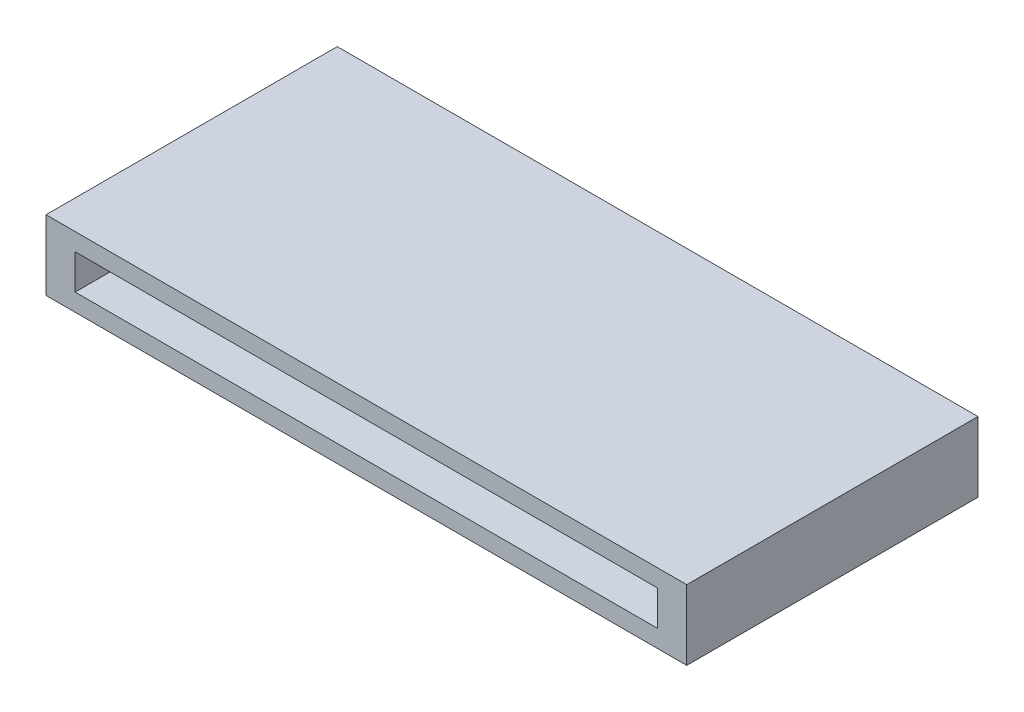
SolidWorks part; units mm, degrees
ref_plane "前视基准面" through (0, 0, 0) normal (0, 0, 1) x (1, 0, 0)
ref_plane "上视基准面" through (0, 0, 0) normal (0, 1, 0) x (1, 0, 0)
ref_plane "右视基准面" through (0, 0, 0) normal (1, 0, 0) x (0, 0, -1)
sketch "草图1" plane through (0, 0, 0) normal (0, 0, 1) x (1, 0, 0)
  line L1 (-5, -0.3) -> (5, -0.3)
  line L2 (-5, -0.3) -> (-5, 0.3)
  line L3 (-5, 0.3) -> (5, 0.3)
  line L4 (5, -0.3) -> (5, 0.3)
  line L5 (-5, -0.3) -> (5, 0.3) construction
  line L6 (-5, 0.3) -> (5, -0.3) construction
  line L7 (-5.5, 0.6) -> (5.5, 0.6)
  line L8 (-5.5, 0.6) -> (-5.5, -0.6)
  line L9 (-5.5, -0.6) -> (5.5, -0.6)
  line L10 (5.5, 0.6) -> (5.5, -0.6)
  line L11 (-5.5, 0.6) -> (5.5, -0.6) construction
  line L12 (-5.5, -0.6) -> (5.5, 0.6) construction
  point P0 (0, 0)
  point P6 (0, 0)
extrude "凸台-拉伸1" add sketch "草图1" along normal blind 5
